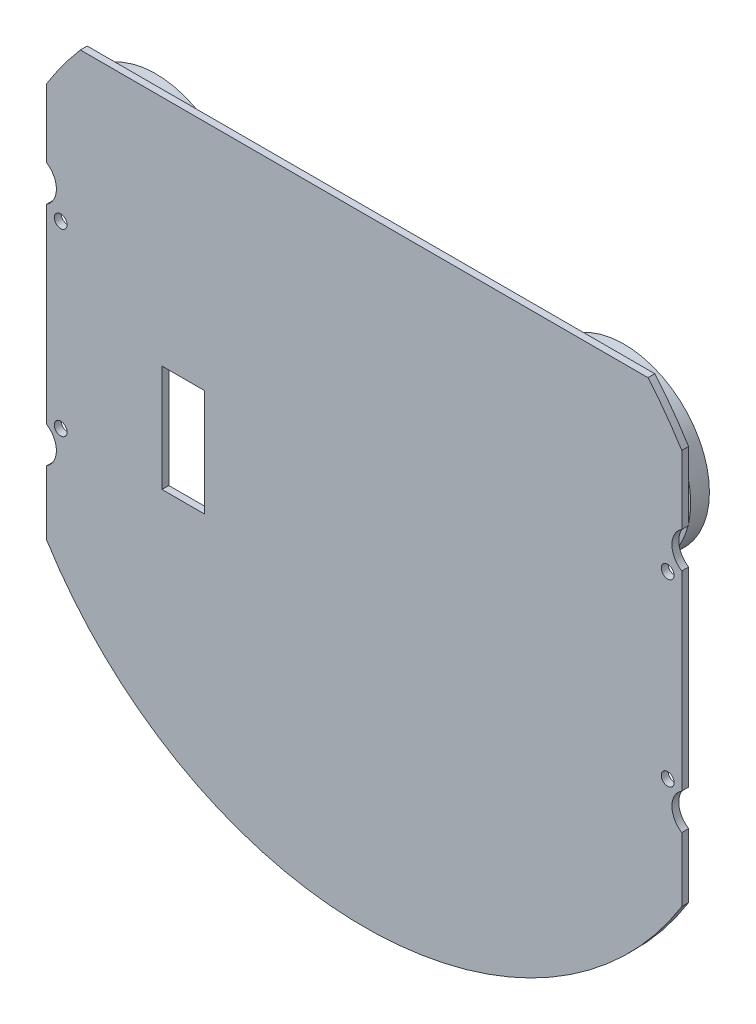
SolidWorks part; units mm, degrees
material "2A12"
ref_plane "前视基准面" through (0, 0, 0) normal (0, 0, 1) x (1, 0, 0)
ref_plane "上视基准面" through (0, 0, 0) normal (0, 1, 0) x (1, 0, 0)
ref_plane "右视基准面" through (0, 0, 0) normal (1, 0, 0) x (0, 0, -1)
sketch "草图1" plane through (0, 0, 0) normal (0, 0, 1) x (1, 0, 0)
  line L0 (-66.3871, 57) -> (66.3871, 57)
  line L1 (0, 0) -> (0, 57) construction
  line L2 (-35, -54.772) -> (35, -54.772) construction
  arc A0 (-66.3871, 57) -> (66.3871, 57) centre (0, 0) ccw
  circle A1 centre (0, 0) radius 25
  circle A2 centre (54.772, 35) radius 20
  circle A3 centre (-54.772, 35) radius 20
  circle A4 centre (35, -54.772) radius 20
  circle A5 centre (-35, -54.772) radius 20
  dimension "D1" = 175
  dimension "D2" = 50
  dimension "D4" = 40
  dimension "D5" = 35
  dimension "D6" = 54.772
  dimension "D7" = 54.772
  dimension "D8" = 35
  dimension "D9" = 35
  dimension "D3" = 57
extrude "凸台-拉伸1" add sketch "草图1" along normal blind 1.6
hole_wizard "Ø3.9 (3.9) 直径孔1" [suppressed] positions "草图3" profile "草图2" hole size "Ø3.9" standard "GB"
sketch "草图3" plane through (0, 0, 0) normal (0, 0, -1) x (-1, 0, 0)
  point P0 (-77, 26)
  point P2 (-77, -27)
  point P4 (77, -27)
  point P6 (77, 26)
sketch "草图2" plane through (77, 26, 0) normal (1, 0, 0) x (0, 1, 0)
  line L0 (0, 0) -> (0, 1)
  line L1 (0, 1) -> (1.95, 1)
  line L2 (1.95, 1) -> (1.95, 0)
  line L5 (1.95, 0) -> (0, 0)
  line L11 (0, -6.35) -> (0, 107.95) construction
  dimension "通孔孔直径" = 3.9
  dimension "通孔孔深度" = 1
sketch "草图4" plane through (0, 0, 1.6) normal (0, 0, 1) x (1, 0, 0)
  circle A0 centre (-54.772, 35) radius 20
  circle A1 centre (0, 0) radius 25
  circle A2 centre (54.772, 35) radius 20
  circle A3 centre (-35, -54.772) radius 20
  circle A4 centre (35, -54.772) radius 20
  dimension "D1" = 40
extrude "凸台-拉伸2" add sketch "草图4" against normal blind 6
sketch "草图5" plane through (0, 0, 0) normal (0, 0, -1) x (-1, 0, 0)
  line L1 (74.3, -100) -> (-74.3, -100)
  line L2 (74.3, -100) -> (74.3, 100)
  line L3 (74.3, 100) -> (-74.3, 100)
  line L4 (-74.3, -100) -> (-74.3, 100)
  line L5 (74.3, -100) -> (-74.3, 100) construction
  line L6 (74.3, 100) -> (-74.3, -100) construction
  point P0 (0, 0)
  dimension "D1" = 148.6
  dimension "D2" = 200
extrude "切除-拉伸1" cut sketch "草图5" against normal blind 10 flip side to cut
sketch "草图6" plane through (0, 0, 0) normal (0, 0, -1) x (-1, 0, 0)
  circle A0 centre (-77, -27) radius 5
  circle A1 centre (-77, 26) radius 5
  circle A2 centre (77, 26) radius 5
  circle A3 centre (77, -27) radius 5
  dimension "D1" = 10
extrude "切除-拉伸2" cut sketch "草图6" against normal blind 10
sketch "草图8" plane through (0, 0, 1.6) normal (0, 0, 1) x (1, 0, 0)
  line L0 (0, 0) -> (0, -10) construction
  line L1 (0, -10) -> (-42.3, -10) construction
  line L2 (-74.3, -22.7917) -> (-74.3, 21.7917) construction
  line L3 (-47.3, -22.5) -> (-37.3, -22.5)
  line L4 (-47.3, -22.5) -> (-47.3, 2.5)
  line L5 (-47.3, 2.5) -> (-37.3, 2.5)
  line L6 (-37.3, -22.5) -> (-37.3, 2.5)
  line L7 (-47.3, -22.5) -> (-37.3, 2.5) construction
  line L8 (-47.3, 2.5) -> (-37.3, -22.5) construction
  circle A0 centre (0, 0) radius 25 construction
  dimension "D1" = 50
  dimension "D2" = 10
  dimension "D3" = 10
  dimension "D4" = 25
  dimension "D5" = 27
extrude "切除-拉伸4" cut sketch "草图8" against normal blind 10
sketch "草图9" plane through (0, 0, 0) normal (0, 0, -1) x (-1, 0, 0)
  circle A0 centre (-71, 20) radius 1.5
  circle A1 centre (-71, -22) radius 1.5
  circle A2 centre (71, 20) radius 1.5
  circle A3 centre (71, -22) radius 1.5
  dimension "D1" = 20
  dimension "D2" = 22
  dimension "D3" = 71
  dimension "D4" = 20
  dimension "D5" = 22
  dimension "D6" = 71
  dimension "D7" = 71
  dimension "D8" = 71
  dimension "D9" = 3
  dimension "D10" = 3
  dimension "D11" = 3
  dimension "D12" = 3
extrude "切除-拉伸5" cut sketch "草图9" against normal through all
